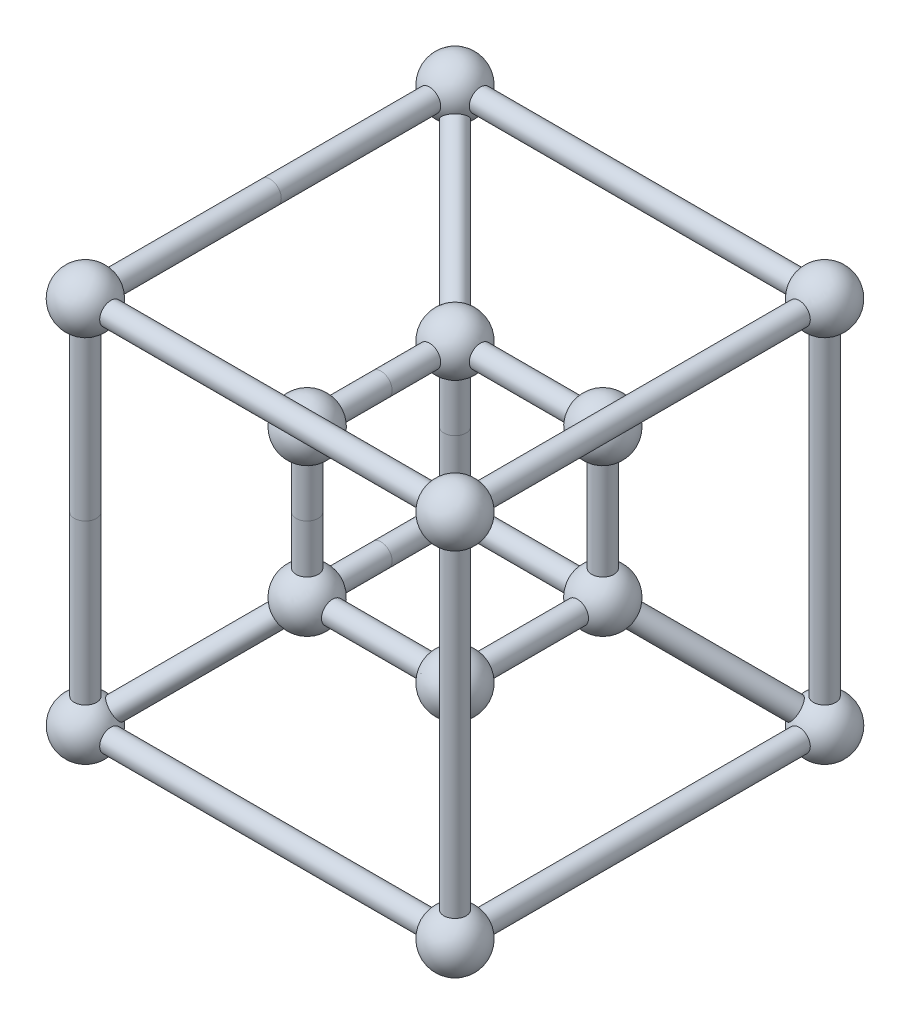
SolidWorks part; units mm, degrees
ref_plane "前视基准面" through (0, 0, 0) normal (0, 0, 1) x (1, 0, 0)
ref_plane "上视基准面" through (0, 0, 0) normal (0, 1, 0) x (1, 0, 0)
ref_plane "右视基准面" through (0, 0, 0) normal (1, 0, 0) x (0, 0, -1)
other "Configuration Table"
sketch "草图1" plane through (0, 0, 0) normal (0, 1, 0) x (1, 0, 0)
  line L0 (0, 0) -> (50, 0) construction
  line L1 (-50, 50) -> (50, 50)
  line L2 (-50, 50) -> (-50, -50)
  line L3 (-50, -50) -> (50, -50)
  line L4 (50, 50) -> (50, -50)
  line L5 (-50, 50) -> (50, -50) construction
  line L6 (-50, -50) -> (50, 50) construction
  line L7 (0, 0) -> (-50, 0) construction
  line L8 (0, 50) -> (0, 0) construction
  line L9 (0, 0) -> (0, -50) construction
  point P0 (0, 0)
  dimension "D1" = 100
sketch "草图9" plane through (0, 0, 0) normal (0, 0, 1) x (1, 0, 0)
  line L0 (-50, 50) -> (-50, 0) construction
  line L1 (-50, 0) -> (-50, -50) construction
  line L2 (-50, -50) -> (0, 0) construction
  line L3 (0, 0) -> (-50, 50) construction
  line L4 (-20, -20) -> (-20, 20) construction
  circle A0 centre (-50, 50) radius 3
  circle A1 centre (-20, 20) radius 3
  circle A2 centre (-20, -20) radius 3
  circle A3 centre (-50, -50) radius 3
  dimension "D3" = 6
  dimension "D1" = 100
  dimension "D2" = 30
sweep "扫描12" add profiles "草图9" path "草图1"
ref_plane "基准面2" through (0, 0, 0) normal (-0.7071, 0, 0.7071) x (0.7071, 0, 0.7071)
sketch "草图11" plane through (0, 0, 0) normal (-0.7071, 0, 0.7071) x (0.7071, 0, 0.7071)
  line L0 (-83.8897, -59.319) -> (84.2642, 59.5838) construction
  line L1 (-66.8302, -43.5819) -> (-35.6288, -21.5191)
  line L2 (32.1647, 26.4181) -> (63.3661, 48.4809)
  arc A0 (-66.8302, -43.5819) -> (-76.8344, -54.3301) centre (-70.7107, -50) ccw
  arc A1 (-22.1605, -15.6699) -> (-35.6288, -21.5191) centre (-28.2843, -20) ccw
  arc A2 (32.1647, 26.4181) -> (22.1605, 15.6699) centre (28.2843, 20) ccw
  arc A3 (76.8344, 54.3301) -> (63.3661, 48.4809) centre (70.7107, 50) ccw
  ellipse E0 centre (-70.7107, -50) end of major axis (-66.468, -50) minor radius 3 construction
  ellipse E1 centre (-28.2843, -20) end of major axis (-24.0416, -20) minor radius 3 construction
  ellipse E2 centre (28.2843, 20) end of major axis (24.0416, 20) minor radius 3 construction
  ellipse E3 centre (70.7107, 50) end of major axis (74.9533, 50) minor radius 3 construction
  dimension "D1" = 15
  dimension "D2" = 3
revolve "旋转9" add sketch "草图11" angle 360 about L0
pattern_circular "阵列(圆周)1" count 4 over 360 about axis through (0, 0, 0) along (1, 0, 0) of "扫描12", "旋转9"
